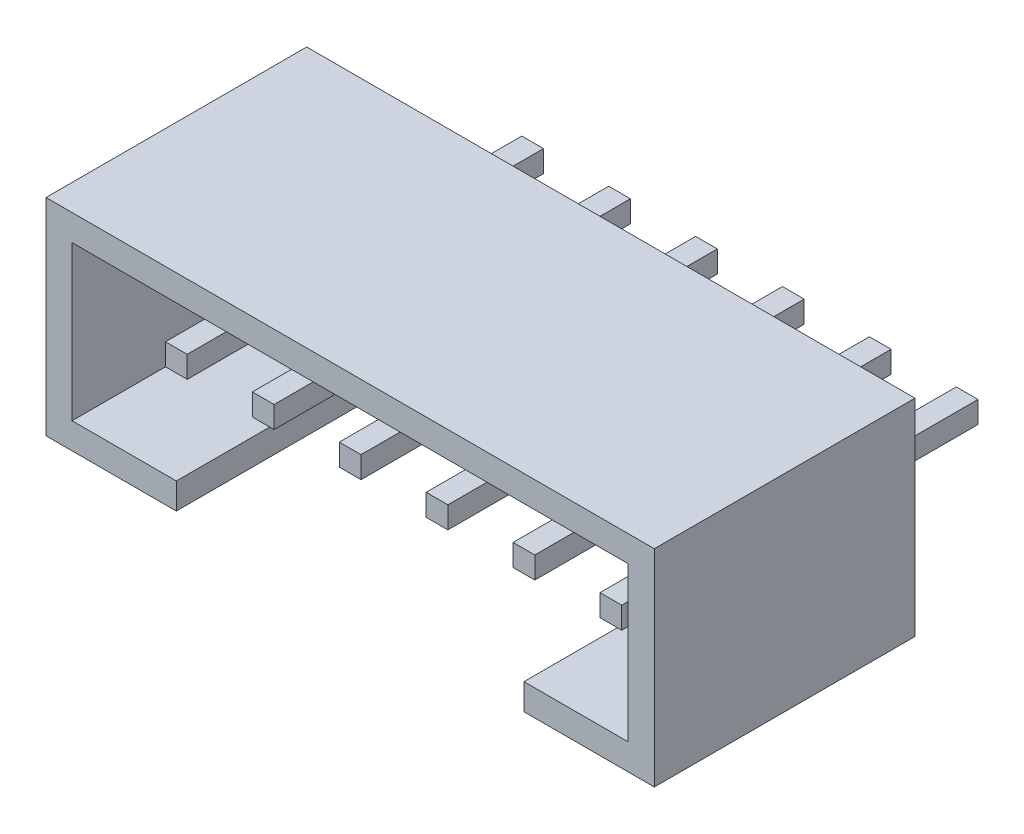
SolidWorks part; units mm, degrees
ref_plane "Front Plane" through (0, 0, 0) normal (0, 0, 1) x (1, 0, 0)
ref_plane "Top Plane" through (0, 0, 0) normal (0, 1, 0) x (1, 0, 0)
ref_plane "Right Plane" through (0, 0, 0) normal (1, 0, 0) x (0, 0, -1)
sketch "Sketch1" plane through (0, 0, 0) normal (0, 0, 1) x (1, 0, 0)
  line L1 (-7, 2.375) -> (7, 2.375)
  line L2 (-7, 2.375) -> (-7, -2.375)
  line L3 (-7, -2.375) -> (7, -2.375)
  line L4 (7, 2.375) -> (7, -2.375)
  line L5 (-7, 2.375) -> (7, -2.375) construction
  line L6 (-7, -2.375) -> (7, 2.375) construction
  point P0 (0, 0)
  dimension "D1" = 14
  dimension "D2" = 4.75
extrude "Boss-Extrude1" add sketch "Sketch1" along normal blind 1.8
sketch "Sketch2" plane through (0, 0, 1.8) normal (0, 0, 1) x (1, 0, 0)
  line L0 (-4, -2.375) -> (-4, -1.775)
  line L1 (-7, -2.375) -> (7, -2.375) construction
  line L2 (-4, -1.775) -> (-6.4, -1.775)
  line L3 (-6.4, -1.775) -> (-6.4, 1.775)
  line L4 (-6.4, 1.775) -> (6.4, 1.775)
  line L5 (0, 1.775) -> (0, 0) construction
  line L6 (-4, -2.375) -> (-7, -2.375)
  line L7 (-7, -2.375) -> (-7, 2.375)
  line L8 (-7, 2.375) -> (7, 2.375)
  line L9 (7, 2.375) -> (-7, 2.375) construction
  line L10 (7, -2.375) -> (7, 2.375)
  line L11 (4, -2.375) -> (7, -2.375)
  line L12 (4, -2.375) -> (4, -1.775)
  line L13 (4, -1.775) -> (6.4, -1.775)
  line L14 (6.4, -1.775) -> (6.4, 1.775)
  point P22 (0, 2.375)
  dimension "D1" = 3
  dimension "D2" = 0.6
  dimension "D3" = 0.6
  dimension "D4" = 0.6
extrude "Boss-Extrude2" add sketch "Sketch2" along normal offset from surface (4.2 mm away) 6 up to face at (0, 0, 0)
sketch "Sketch3" plane through (0, 0, 1.8) normal (0, 0, 1) x (1, 0, 0)
  line L0 (-4, -2.375) -> (4, -2.375) construction
  line L1 (-5.25, -0.125) -> (-4.75, -0.125)
  line L2 (-5.25, -0.125) -> (-5.25, -0.625)
  line L3 (-5.25, -0.625) -> (-4.75, -0.625)
  line L4 (-4.75, -0.125) -> (-4.75, -0.625)
  point P4 (-5.25, -0.375)
  point P7 (-5, -0.625)
  dimension "D1" = 0.5
  dimension "D2" = 2
  dimension "D3" = 5
extrude "Boss-Extrude3" add sketch "Sketch3" along normal offset from surface 5 and the other way blind 5 up to face at (0, 0, 0)
pattern_linear "LPattern1" count 6 spacing 2 along (1, 0, 0) of "Boss-Extrude3"
